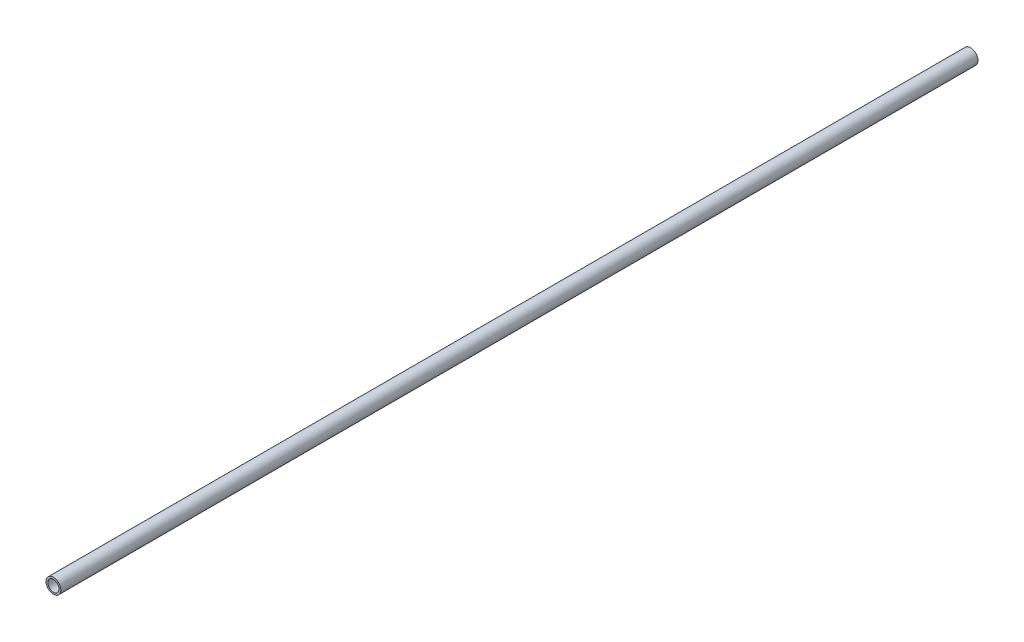
SolidWorks part; units mm, degrees
material "Thornel Mat VMA"
ref_plane "Front Plane" through (0, 0, 0) normal (0, 0, 1) x (1, 0, 0)
ref_plane "Top Plane" through (0, 0, 0) normal (0, 1, 0) x (1, 0, 0)
ref_plane "Right Plane" through (0, 0, 0) normal (1, 0, 0) x (0, 0, -1)
sketch "Sketch1" plane through (0, 0, 0) normal (0, 0, 1) x (1, 0, 0)
  circle A0 centre (-6.8053, 9.037) radius 2
  circle A1 centre (-6.8053, 9.037) radius 1.5
  dimension "D1" = 4
  dimension "D2" = 3
extrude "Boss-Extrude1" add sketch "Sketch1" along normal blind 247.65
